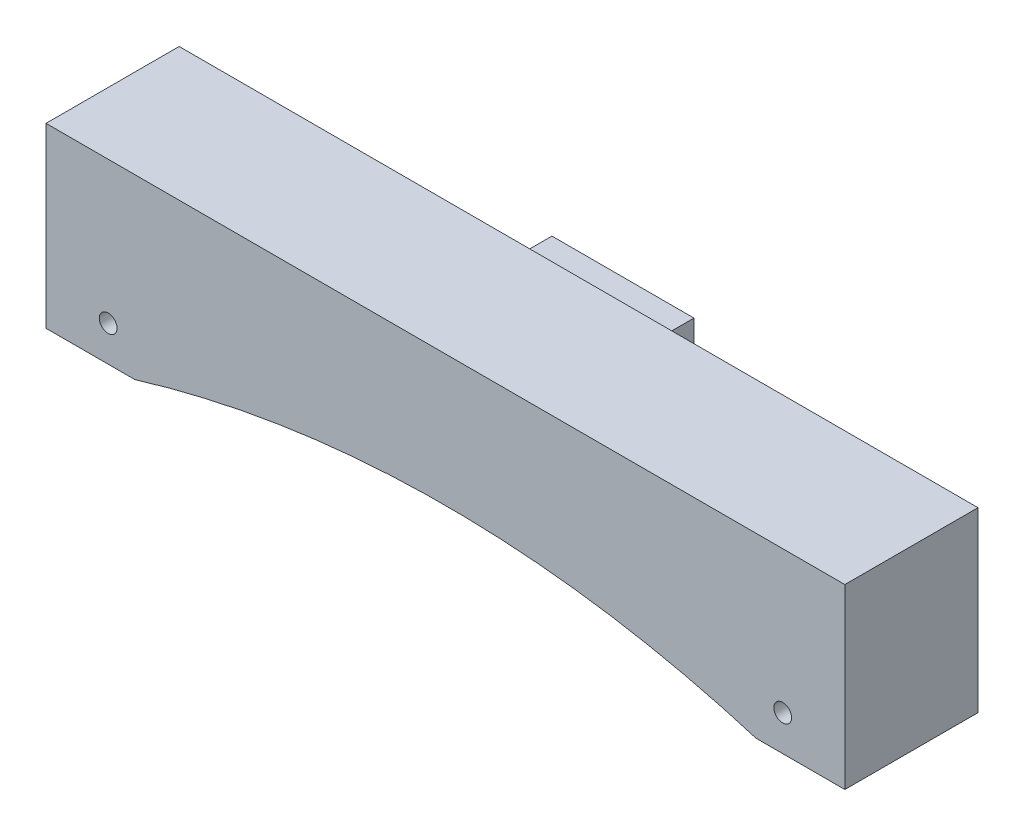
SolidWorks part; units mm, degrees
ref_plane "Front Plane" through (0, 0, 0) normal (0, 0, 1) x (1, 0, 0)
ref_plane "Top Plane" through (0, 0, 0) normal (0, 1, 0) x (1, 0, 0)
ref_plane "Right Plane" through (0, 0, 0) normal (1, 0, 0) x (0, 0, -1)
sketch "Sketch1" plane through (0, 0, 0) normal (0, 0, 1) x (1, 0, 0)
  line L0 (0, 0) -> (90, 0)
  line L1 (90, 0) -> (90, -20)
  line L2 (90, -20) -> (80, -20)
  line L3 (0, 0) -> (0, -20)
  line L4 (0, -20) -> (10, -20)
  arc A0 (80, -20) -> (10, -20) centre (45, -134.7824) ccw
  dimension "D6" = 120
  dimension "D1" = 90
  dimension "D2" = 20
  dimension "D3" = 20
  dimension "D4" = 10
  dimension "D5" = 10
extrude "Boss-Extrude1" add sketch "Sketch1" along normal blind 15
sketch "Sketch2" plane through (0, 0, 15) normal (0, 0, 1) x (1, 0, 0)
  line L0 (0, 0) -> (0, -20) construction
  line L1 (90, -20) -> (90, 0) construction
  line L2 (0, -20) -> (10, -20) construction
  circle A0 centre (7, -16) radius 1
  circle A1 centre (83, -16) radius 1
  point P8 (0, 0)
  dimension "D1" = 2
  dimension "D2" = 2
  dimension "D3" = 7
  dimension "D4" = 7
  dimension "D5" = 4
extrude "Cut-Extrude1" cut sketch "Sketch2" against normal blind 5
sketch "Sketch3" plane through (0, 0, 0) normal (0, 0, -1) x (-1, 0, 0)
  line L0 (0, 0) -> (0, -20) construction
  line L1 (-52.5, -3) -> (-37.5, -3)
  line L2 (-52.5, -3) -> (-52.5, -11)
  line L3 (-52.5, -11) -> (-37.5, -11)
  line L4 (-37.5, -3) -> (-37.5, -11)
  line L5 (-52.5, -3) -> (-37.5, -11) construction
  line L6 (-52.5, -11) -> (-37.5, -3) construction
  line L7 (-53, -11.5) -> (-37, -11.5)
  line L8 (-53, -11.5) -> (-53, -2.5)
  line L9 (-53, -2.5) -> (-37, -2.5)
  line L10 (-37, -11.5) -> (-37, -2.5)
  line L11 (-53, -11.5) -> (-37, -2.5) construction
  line L12 (-53, -2.5) -> (-37, -11.5) construction
  line L13 (-90, 0) -> (0, 0) construction
  point P0 (-45, -7)
  point P5 (-45, -7)
  dimension "D1" = 45
  dimension "D2" = 15
  dimension "D3" = 16
  dimension "D4" = 7
  dimension "D5" = 8
  dimension "D6" = 9
extrude "Boss-Extrude2" add sketch "Sketch3" along normal blind 5
sketch "Sketch4" plane through (0, 0, 0) normal (0, 0, -1) x (-1, 0, 0)
  line L0 (-52.5, -3) -> (-52.5, -11) construction
  line L1 (-37.5, -3) -> (-52.5, -3) construction
  circle A0 centre (-45, -7) radius 1
  dimension "D1" = 2
  dimension "D2" = 7.5
  dimension "D3" = 4
extrude "Cut-Extrude2" cut sketch "Sketch4" against normal blind 5
